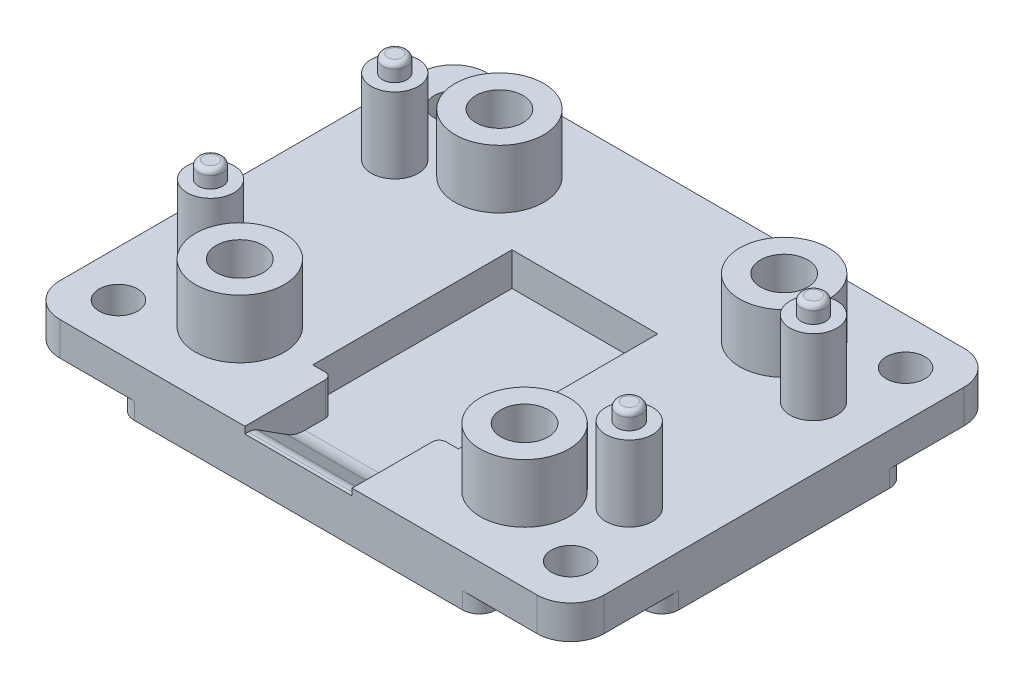
SolidWorks part; units mm, degrees
material "尼龙 101"
ref_plane "前视基准面" through (0, 0, 0) normal (0, 0, 1) x (1, 0, 0)
ref_plane "上视基准面" through (0, 0, 0) normal (0, 1, 0) x (1, 0, 0)
ref_plane "右视基准面" through (0, 0, 0) normal (1, 0, 0) x (0, 0, -1)
other "Configuration Table"
sketch "草图1" plane through (0, 0, 0) normal (0, 1, 0) x (1, 0, 0)
  line L1 (-16.25, 12.75) -> (16.25, 12.75)
  line L2 (-16.25, 12.75) -> (-16.25, -12.75)
  line L3 (-16.25, -12.75) -> (16.25, -12.75)
  line L4 (16.25, 12.75) -> (16.25, -12.75)
  line L5 (-16.25, 12.75) -> (16.25, -12.75) construction
  line L6 (-16.25, -12.75) -> (16.25, 12.75) construction
  point P0 (0, 0)
  dimension "D1" = 32.5
  dimension "D2" = 25.5
extrude "凸台-拉伸1" add sketch "草图1" along normal blind 3
sketch "草图2" plane through (0, 3, 0) normal (0, 1, 0) x (1, 0, 0)
  line L0 (0, 0) -> (0, 5.35) construction
  line L1 (-5.35, 5.35) -> (5.35, 5.35)
  line L2 (5.35, 5.35) -> (5.35, -7.55)
  line L3 (5.35, -7.55) -> (4.35, -7.55)
  line L4 (4.35, -7.55) -> (4.35, 4.35)
  line L5 (4.35, 4.35) -> (-4.35, 4.35)
  line L6 (-4.35, -7.55) -> (-4.35, 4.35)
  line L7 (-5.35, -7.55) -> (-4.35, -7.55)
  line L8 (-5.35, 5.35) -> (-5.35, -7.55)
  point P9 (0, 4.35)
  dimension "D1" = 8.7
  dimension "D2" = 11.9
  dimension "D3" = 4.35
  dimension "D4" = 1
  dimension "D5" = 1
extrude "凸台-拉伸2" add sketch "草图2" along normal blind 1.5
sketch "草图5" plane through (0, 3, 0) normal (0, 1, 0) x (1, 0, 0)
  line L0 (0, 12.75) -> (0, 0) construction
  line L1 (16.25, 12.75) -> (-16.25, 12.75) construction
  line L2 (0, 0) -> (16.25, 0) construction
  line L3 (16.25, -12.75) -> (16.25, 12.75) construction
  circle A0 centre (12.5, 5.5) radius 1.4
  circle A1 centre (12.5, -5.5) radius 1.4
  circle A2 centre (-12.5, -5.5) radius 1.4
  circle A3 centre (-12.5, 5.5) radius 1.4
  dimension "D1" = 2.8
  dimension "D2" = 25
  dimension "D3" = 11
extrude "凸台-拉伸3" add sketch "草图5" along normal blind 4.5
sketch "草图6" plane through (0, 7.5, 0) normal (0, 1, 0) x (1, 0, 0)
  circle A0 centre (-12.5, -5.5) radius 0.725
  circle A1 centre (-12.5, 5.5) radius 0.725
  circle A2 centre (12.5, 5.5) radius 0.725
  circle A3 centre (12.5, -5.5) radius 0.725
  dimension "D1" = 1.45
extrude "凸台-拉伸4" add sketch "草图6" along normal blind 1
sketch "草图7" plane through (0, 3, 0) normal (0, 1, 0) x (1, 0, 0)
  line L0 (0, 0) -> (0, 12.75) construction
  line L1 (16.25, 12.75) -> (-16.25, 12.75) construction
  line L2 (0, 0) -> (16.25, 0) construction
  line L3 (16.25, -12.75) -> (16.25, 12.75) construction
  circle A0 centre (13.5, 10) radius 1
  circle A1 centre (-13.5, 10) radius 1
  circle A2 centre (-13.5, -10) radius 1
  circle A3 centre (13.5, -10) radius 1
  dimension "D1" = 2
  dimension "D2" = 20
  dimension "D3" = 27
extrude "切除-拉伸1" cut sketch "草图7" against normal blind 10
sketch "草图8" plane through (0, 0, 0) normal (0, -1, 0) x (1, 0, 0)
  circle A0 centre (-13.5, 10) radius 2
  circle A1 centre (13.5, 10) radius 2
  circle A2 centre (13.5, -10) radius 2
  circle A3 centre (-13.5, -10) radius 2
  dimension "D1" = 4
extrude "切除-拉伸2" cut sketch "草图8" against normal blind 1
fillet "圆角1" radius 2 4 edges at (-16.25, 1.5, -12.75) (16.25, 1.5, -12.75) (-16.25, 1.5, 12.75) (16.25, 1.5, 12.75)
sketch "草图9" plane through (0, 3, 0) normal (0, 1, 0) x (1, 0, 0)
  line L0 (0, 12.75) -> (0, 0) construction
  line L1 (14.25, 12.75) -> (-14.25, 12.75) construction
  line L2 (0, 0) -> (16.25, 0) construction
  line L3 (16.25, -10.75) -> (16.25, 10.75) construction
  circle A0 centre (8.5, 7.75) radius 2.65
  circle A1 centre (-8.5, 7.75) radius 2.65
  circle A2 centre (-8.5, -7.75) radius 2.65
  circle A3 centre (8.5, -7.75) radius 2.65
  dimension "D1" = 17
  dimension "D2" = 15.5
  dimension "D3" = 5.3
extrude "凸台-拉伸5" add sketch "草图9" along normal blind 3.5
sketch "草图11" plane through (0, 6.5, 0) normal (0, 1, 0) x (1, 0, 0)
  circle A0 centre (-8.5, 7.75) radius 1.05
  circle A1 centre (-8.5, -7.75) radius 1.05
  circle A2 centre (8.5, -7.75) radius 1.05
  circle A3 centre (8.5, 7.75) radius 1.05
  dimension "D1" = 2.1
extrude "切除-拉伸4" cut sketch "草图11" against normal blind 100
sketch "草图12" plane through (0, 6.5, 0) normal (0, 1, 0) x (1, 0, 0)
  circle A0 centre (-8.5, 7.75) radius 1.41
  circle A1 centre (8.5, 7.75) radius 1.41
  circle A2 centre (-8.5, -7.75) radius 1.41
  circle A3 centre (8.5, -7.75) radius 1.41
  dimension "D1" = 2.82
extrude "切除-拉伸5" cut sketch "草图12" against normal blind 5.5
fillet "圆角2" radius 0.3 4 edges at (12.5, 8.5, -4.775) (12.5, 8.5, 6.225) (-12.5, 8.5, 6.225) (-12.5, 8.5, -4.775)
sketch "草图15" plane through (0, 3, 0) normal (0, 1, 0) x (1, 0, 0)
  line L0 (0, 0) -> (0, 12.75) construction
  line L1 (14.25, 12.75) -> (-14.25, 12.75) construction
  line L2 (-4.35, 4.35) -> (4.35, 4.35)
  line L3 (4.35, 4.35) -> (4.35, -7.55)
  line L4 (4.35, -7.55) -> (3.2, -7.55)
  line L5 (3.2, -7.55) -> (3.2, -12.75)
  line L6 (-14.25, -12.75) -> (14.25, -12.75) construction
  line L7 (3.2, -12.75) -> (-3.2, -12.75)
  line L8 (-3.2, -7.55) -> (-3.2, -12.75)
  line L9 (-4.35, -7.55) -> (-3.2, -7.55)
  line L10 (-4.35, 4.35) -> (-4.35, -7.55)
  line L11 (4.35, 4.35) -> (4.35, -7.55) construction
  point P14 (0, -12.75)
  point P17 (0, 4.35)
  dimension "D1" = 6.4
extrude "切除-拉伸8" cut sketch "草图15" against normal blind 2
sketch "草图17" plane through (0, 4.5, 0) normal (0, 1, 0) x (1, 0, 0)
  line L8 (-4.35, -7.55) -> (-4.35, 4.35)
  line L9 (-4.35, 4.35) -> (4.35, 4.35)
  line L10 (4.35, 4.35) -> (4.35, -7.55)
  line L11 (4.35, -7.55) -> (5.35, -7.55)
  line L12 (5.35, -7.55) -> (5.35, 5.35)
  line L13 (5.35, 5.35) -> (-5.35, 5.35)
  line L14 (-5.35, 5.35) -> (-5.35, -7.55)
  line L15 (-5.35, -7.55) -> (-4.35, -7.55)
  line L16 (-4.35, -7.55) -> (-4.35, 4.35)
  line L17 (-4.35, 4.35) -> (4.35, 4.35)
  line L18 (4.35, 4.35) -> (4.35, -7.55)
  line L19 (4.35, -7.55) -> (5.35, -7.55)
  line L20 (5.35, -7.55) -> (5.35, 5.35)
  line L21 (5.35, 5.35) -> (-5.35, 5.35)
  line L22 (-5.35, 5.35) -> (-5.35, -7.55)
  line L23 (-5.35, -7.55) -> (-4.35, -7.55)
  dimension "D1" = 0
extrude "切除-拉伸9" cut sketch "草图17" against normal blind 1.5
sketch "草图18" plane through (3.2, 0, 0) normal (-1, 0, 0) x (0, 0, 1)
  line L0 (12.75, 1) -> (9.75, 1)
  line L2 (12.75, 1) -> (12.75, 3) construction
  line L3 (12.75, 2.6) -> (12.75, 1)
  line L5 (12.75, 3) -> (12.75, 0) construction
  line L6 (12.75, 2.6) -> (12.25, 2.6)
  line L7 (12.25, 2.6) -> (9.75, 1)
  line L8 (12.75, 3) -> (10.75, 3) construction
  dimension "D1" = 3
  dimension "D2" = 0.4
  dimension "D3" = 0.5
extrude "凸台-拉伸6" add sketch "草图18" along normal up to surface (6.4 mm away) up to face at (-3.2, 2, 10.15)
fillet "圆角3" radius 2 1 edges at (0, 1, 9.75)
fillet "圆角5" radius 1 1 edges at (0, 2.6, 12.25)
fillet "圆角6" radius 0.4 2 edges at (3.2, 2, 7.55) (-3.2, 2, 7.55)
sketch "草图21" plane through (0, 0, 0) normal (0, -1, 0) x (1, 0, 0)
  line L1 (-13.5, -7.3) -> (-10.8, -7.3)
  line L2 (-10.8, -7.3) -> (-10.8, -12.75)
  line L3 (14.25, -12.75) -> (-14.25, -12.75) construction
  line L4 (-10.8, -12.75) -> (-16.25, -12.75)
  line L5 (-16.25, -12.75) -> (-16.25, -7.3)
  line L6 (-16.25, -10.75) -> (-16.25, 10.75) construction
  line L7 (-16.25, -7.3) -> (-13.5, -7.3)
  line L11 (16.25, -12.75) -> (16.25, -7.3)
  line L12 (10.8, -12.75) -> (16.25, -12.75)
  line L13 (10.8, -7.3) -> (10.8, -12.75)
  line L14 (13.5, -7.3) -> (10.8, -7.3)
  line L15 (16.25, -7.3) -> (13.5, -7.3)
  line L16 (16.25, 12.75) -> (16.25, 7.3)
  line L17 (10.8, 12.75) -> (16.25, 12.75)
  line L18 (10.8, 7.3) -> (10.8, 12.75)
  line L19 (16.25, 7.3) -> (13.5, 7.3)
  line L20 (13.5, 7.3) -> (10.8, 7.3)
  line L21 (-10.8, 12.75) -> (-16.25, 12.75)
  line L22 (-16.25, 12.75) -> (-16.25, 7.3)
  line L23 (-16.25, 7.3) -> (-13.5, 7.3)
  line L24 (-13.5, 7.3) -> (-10.8, 7.3)
  line L25 (-10.8, 7.3) -> (-10.8, 12.75)
ref_plane "基准面1" through (0, 0, 0) normal (-1, 0, 0) x (0, 0, 1)
ref_plane "基准面2" through (0, 0, 0) normal (0, 0, -1) x (-1, 0, 0)
extrude "切除-拉伸13" cut sketch "草图21" against normal blind 1
fillet "圆角7" radius 1 12 edges at (-16.25, 0.5, 7.3) (-10.8, 0.5, 7.3) (-10.8, 0.5, 12.75) (-10.8, 0.5, -12.75) (-16.25, 0.5, -7.3) (-10.8, 0.5, -7.3) (10.8, 0.5, -12.75) (10.8, 0.5, -7.3) (16.25, 0.5, -7.3) (10.8, 0.5, 7.3) (16.25, 0.5, 7.3) (10.8, 0.5, 12.75)
sketch "草图22" plane through (0, 1, 0) normal (0, -1, 0) x (1, 0, 0)
  circle A0 centre (13.5, -10) radius 1.15
  circle A1 centre (13.5, 10) radius 1.15
  circle A2 centre (-13.5, 10) radius 1.15
  circle A3 centre (-13.5, -10) radius 1.15
extrude "切除-拉伸14" cut sketch "草图22" against normal blind 10
